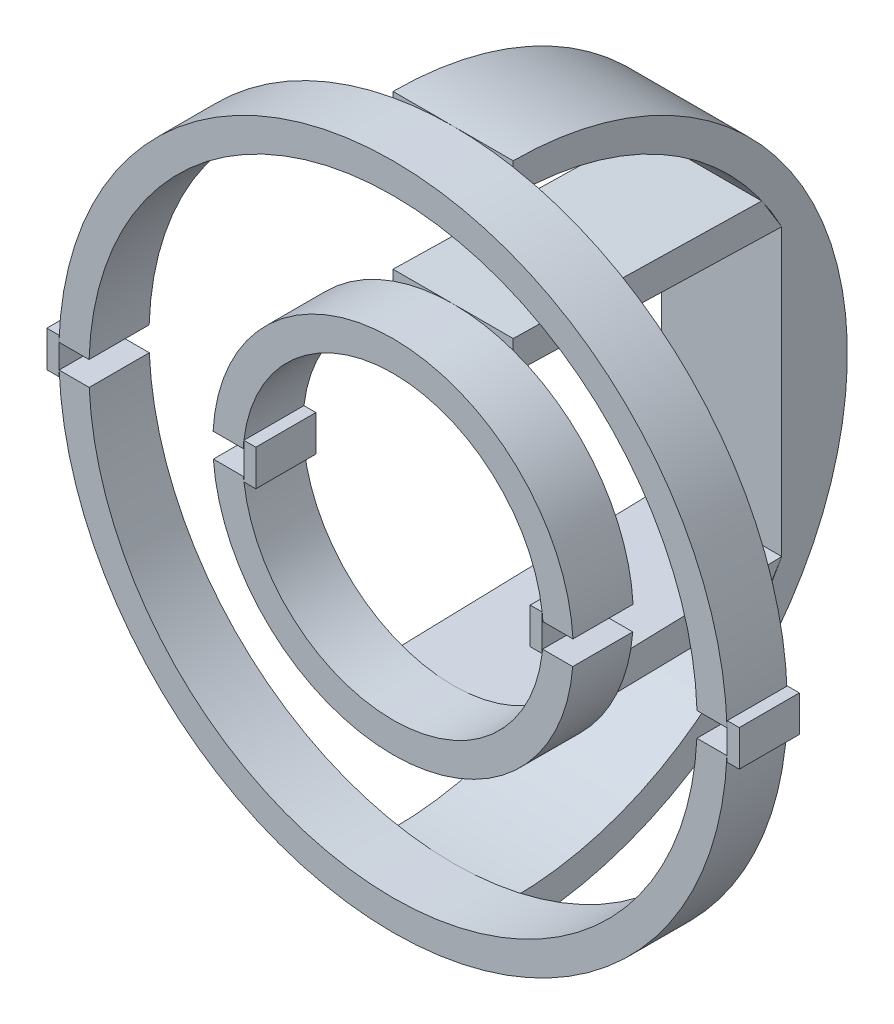
SolidWorks part; units mm, degrees
ref_plane "Front Plane" through (0, 0, 0) normal (0, 0, 1) x (1, 0, 0)
ref_plane "Top Plane" through (0, 0, 0) normal (0, 1, 0) x (1, 0, 0)
ref_plane "Right Plane" through (0, 0, 0) normal (1, 0, 0) x (0, 0, -1)
sketch "Sketch1" plane through (0, 0, 0) normal (0, 0, 1) x (1, 0, 0)
  line L0 (11.1257, 0.5476) -> (11.5257, 0.5476)
  line L13 (11.1257, 0.5476) -> (11.1257, -0.6524)
  line L14 (11.1257, -0.6524) -> (11.5257, -0.6524)
  line L15 (11.5257, 0.5476) -> (11.5257, -0.6524)
  line L16 (-11.5248, 0.5381) -> (-11.1248, 0.5381)
  line L17 (-11.5248, 0.5381) -> (-11.5248, -0.6619)
  line L18 (-11.5248, -0.6619) -> (-11.1248, -0.6619)
  line L19 (-11.1248, 0.5381) -> (-11.1248, -0.6619)
  line L24 (-4.9683, 0.5837) -> (-4.5683, 0.5837)
  line L25 (-4.9683, 0.5837) -> (-4.9683, -0.6163)
  line L26 (-4.9683, -0.6163) -> (-4.5683, -0.6163)
  line L27 (-4.5683, 0.5837) -> (-4.5683, -0.6163)
  line L28 (4.5649, 0.5993) -> (4.9649, 0.5993)
  line L29 (4.5649, 0.5993) -> (4.5649, -0.6007)
  line L30 (4.5649, -0.6007) -> (4.9649, -0.6007)
  line L31 (4.9649, 0.5993) -> (4.9649, -0.6007)
  line L33 (-11.1218, 0.3345) -> (11.1282, 0.3345)
  line L34 (-11.1218, 0.3345) -> (-11.1218, -0.4655)
  line L35 (-11.1218, -0.4655) -> (11.1282, -0.4655)
  line L36 (11.1282, 0.3345) -> (11.1282, -0.4655)
  circle A0 centre (0, 0) radius 11.125
  circle A1 centre (0, 0) radius 10.125
  circle A2 centre (0, 0) radius 6
  circle A3 centre (0, 0) radius 5
  dimension "D1" = 22.25
  dimension "D2" = 20.25
  dimension "D3" = 12
  dimension "D4" = 10
  dimension "D5" = 0.8
  dimension "D6" = 22.25
extrude "Boss-Extrude6" add sketch "Sketch1" along normal blind 2 contours A1 L33 A0 | A1 L35 A0 | A3 L35 A2 L31 L30 L26 L25 | A3 L33 A2 L25 L24 L28 L31 | L17 L18 L19 L16 | L15 L14 L13 L0
sketch "Sketch7" plane through (0, 0, 0) normal (1, 0, 0) x (0, 0, -1)
  line L0 (0, -11.125) -> (0, -0.4655) construction
  line L1 (0, 11.125) -> (0, 10.125)
  line L2 (0, -10.125) -> (0, -11.125)
  line L3 (0, 6) -> (8.2783, 5.8296)
  line L4 (0, 5) -> (8.9395, 4.754)
  line L5 (0, -5) -> (8.9395, -4.754)
  line L6 (0, -6) -> (8.2783, -5.8296)
  line L7 (0, 6) -> (0, 5)
  line L8 (0, -5) -> (0, -6)
  line L9 (8.2783, 5.8296) -> (8.9395, 4.754)
  line L10 (8.9395, -4.754) -> (8.2783, -5.8296)
  line L11 (8.9395, 4.754) -> (8.9395, -4.754)
  arc A0 (0, 11.125) -> (0, -11.125) centre (0, 0) cw
  arc A1 (0, 10.125) -> (0, -10.125) centre (0, 0) cw
  arc A2 (8.9395, 4.754) -> (8.9395, -4.754) centre (0, 0) cw
extrude "Boss-Extrude9" add sketch "Sketch7" along normal mid plane 4 contours L10 L5 L8 L6 | L9 L3 L7 L4 | A1 L2 A0 L1 | A1 L11
